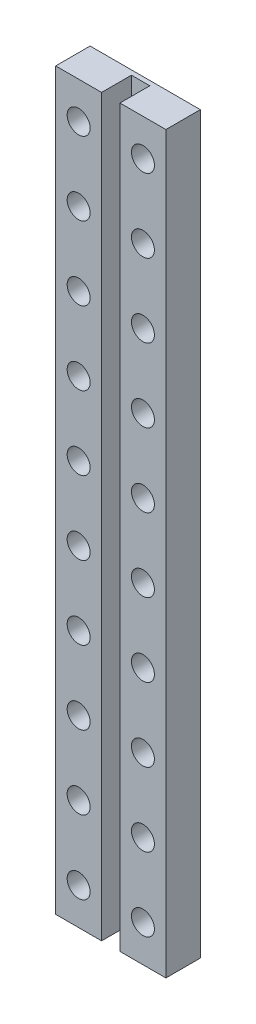
SolidWorks part; units mm, degrees
ref_plane "Plan de face" through (0, 0, 0) normal (0, 0, 1) x (1, 0, 0)
ref_plane "Plan de dessus" through (0, 0, 0) normal (0, 1, 0) x (1, 0, 0)
ref_plane "Plan de droite" through (0, 0, 0) normal (1, 0, 0) x (0, 0, -1)
sketch "Esquisse1" plane through (0, 0, 0) normal (0, 1, 0) x (1, 0, 0)
  line L0 (-2, -3.75) -> (-2, 2.75)
  line L1 (12, 3.75) -> (-12, 3.75)
  line L2 (12, 3.75) -> (12, -3.75)
  line L3 (12, -3.75) -> (2, -3.75)
  line L4 (-12, 3.75) -> (-12, -3.75)
  line L5 (12, 3.75) -> (-12, -3.75) construction
  line L6 (12, -3.75) -> (-12, 3.75) construction
  line L7 (-2, 2.75) -> (2, 2.75)
  line L8 (2, 2.75) -> (2, -3.75)
  line L9 (-2, 2.75) -> (2, -3.75) construction
  line L10 (0, 1.5046) -> (0, -2.3161) construction
  line L11 (-2, -3.75) -> (-12, -3.75)
  point P0 (0, 0)
  point P8 (0, -0.5)
  dimension "D1" = 7.5
  dimension "D2" = 24
  dimension "D3" = 1
  dimension "D4" = 10
extrude "BASE" add sketch "Esquisse1" against normal blind 160
sketch "Esquisse2" plane through (0, 0, 3.75) normal (0, 0, 1) x (1, 0, 0)
  line L0 (-7, 0) -> (-7, -38.4741) construction
  line L1 (-12, 0) -> (-2, 0) construction
  line L2 (-7, -5.5) -> (-4.873, -5.5) construction
  circle A0 centre (-7, -8) radius 2.5
  circle A1 centre (7, -8) radius 2.5
  circle A2 centre (7, -24) radius 2.5
  circle A3 centre (7, -40) radius 2.5
  circle A4 centre (7, -56) radius 2.5
  circle A5 centre (7, -72) radius 2.5
  circle A6 centre (7, -88) radius 2.5
  circle A7 centre (7, -104) radius 2.5
  circle A8 centre (7, -120) radius 2.5
  circle A9 centre (7, -136) radius 2.5
  circle A10 centre (7, -152) radius 2.5
  circle A11 centre (-7, -24) radius 2.5
  circle A12 centre (-7, -40) radius 2.5
  circle A13 centre (-7, -56) radius 2.5
  circle A14 centre (-7, -72) radius 2.5
  circle A15 centre (-7, -88) radius 2.5
  circle A16 centre (-7, -104) radius 2.5
  circle A17 centre (-7, -120) radius 2.5
  circle A18 centre (-7, -136) radius 2.5
  circle A19 centre (-7, -152) radius 2.5
  dimension "D2" = 5
  dimension "D1" = 5.5
  dimension "D3" = 2
  dimension "D4" = 10
extrude "TROU" cut sketch "Esquisse2" against normal through all
